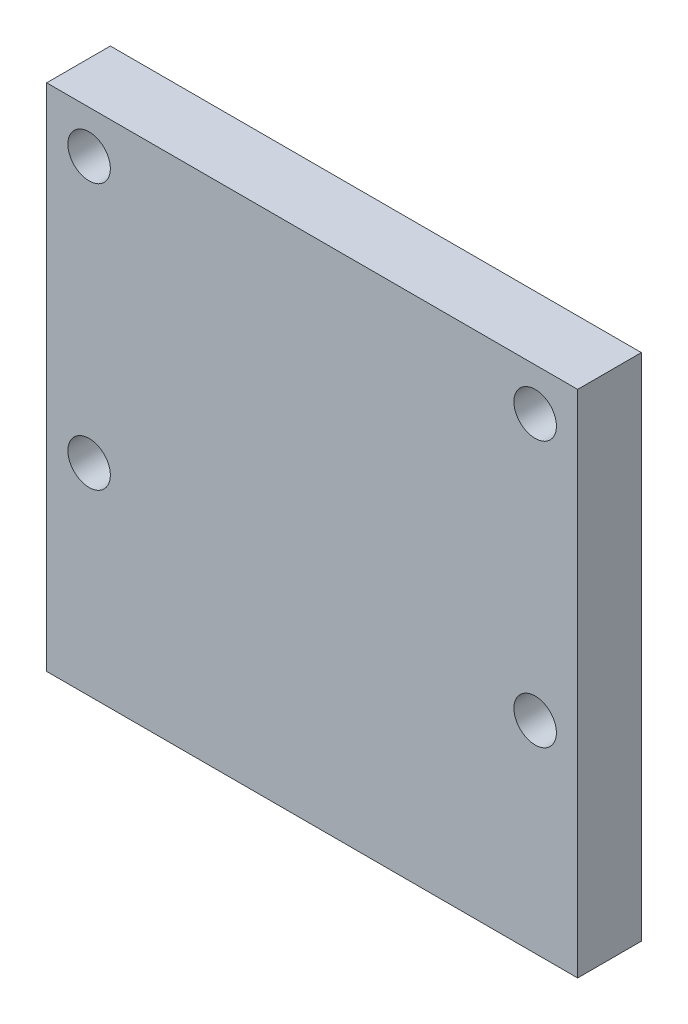
SolidWorks part; units mm, degrees
ref_plane "前视基准面" through (0, 0, 0) normal (0, 0, 1) x (1, 0, 0)
ref_plane "上视基准面" through (0, 0, 0) normal (0, 1, 0) x (1, 0, 0)
ref_plane "右视基准面" through (0, 0, 0) normal (1, 0, 0) x (0, 0, -1)
sketch "草图1" plane through (0, 0, 0) normal (0, 0, 1) x (1, 0, 0)
  line L0 (-14.3954, 12.3162) -> (10.6046, 12.3162)
  line L1 (-14.3954, 12.3162) -> (-14.3954, -11.6838)
  line L2 (10.6046, 12.3162) -> (10.6046, -11.6838)
  line L3 (-14.3954, -11.6838) -> (10.6046, -11.6838)
  dimension "D1" = 25
  dimension "D2" = 24
extrude "凸台-拉伸1" add sketch "草图1" along normal blind 3
sketch "草图8" plane through (0, 0, 3) normal (0, 0, 1) x (1, 0, 0)
  line L0 (10.6046, 12.3162) -> (-14.3954, 12.3162) construction
  line L1 (-14.3954, 12.3162) -> (-14.3954, -11.6838) construction
  line L2 (10.6046, -11.6838) -> (10.6046, 12.3162) construction
  point P0 (-12.3954, 10.3162)
  point P2 (8.6046, 10.3162)
  point P4 (-12.3954, -2.1838)
  point P6 (8.6046, -2.1838)
  dimension "D1" = 2
  dimension "D2" = 2
  dimension "D3" = 2
  dimension "D4" = 2
  dimension "D5" = 2
  dimension "D6" = 2
  dimension "D7" = 12.5
  dimension "D8" = 12.5
hole_wizard "Ø2.0 (2) 直径孔1" positions "草图8" profile "草图7" hole size "Ø2.0" standard "GB"
sketch "草图7" plane through (-12.3954, 10.3162, 3) normal (1, 0, 0) x (0, -1, 0)
  line L0 (0, 0) -> (0, 6.1009)
  line L1 (0, 6.1009) -> (1, 5.5)
  line L2 (1, 5.5) -> (1, 0)
  line L5 (1, 0) -> (0, 0)
  line L10 (0, 6.1009) -> (-1, 5.5) construction
  line L11 (0, -6.35) -> (0, 107.95) construction
  dimension "孔直径" = 2
  dimension "孔深度" = 5.5
  dimension "导头角度" = 118
